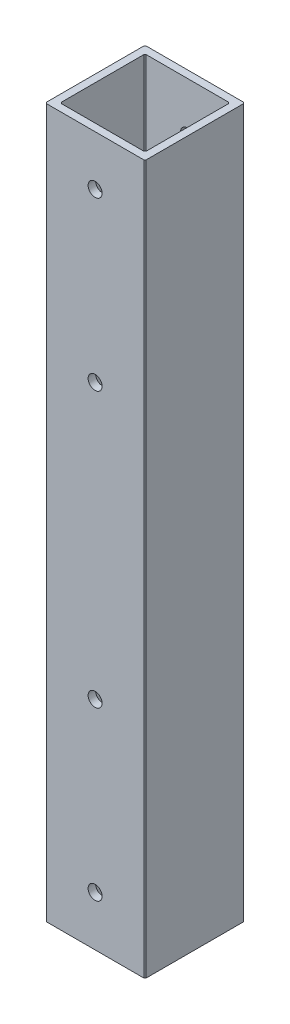
SolidWorks part; units mm, degrees
ref_plane "Front Plane" through (0, 0, 0) normal (0, 0, 1) x (1, 0, 0)
ref_plane "Top Plane" through (0, 0, 0) normal (0, 1, 0) x (1, 0, 0)
ref_plane "Right Plane" through (0, 0, 0) normal (1, 0, 0) x (0, 0, -1)
ref_plane "Plane1" through (170, 0, 0) normal (-1, 0, 0) x (0, -1, 0)
sketch "Sketch1" plane through (170, 0, 0) normal (-1, 0, 0) x (0, -1, 0)
  line L0 (-142, 180) -> (-142, 140)
  line L1 (-142, 140) -> (142, 140)
  line L2 (142, 140) -> (142, 180)
  line L3 (142, 180) -> (-142, 180)
extrude "Boss-Extrude1" add sketch "Sketch1" against normal blind 40
sketch "Sketch2" plane through (0, -142, 0) normal (0, -1, 0) x (1, 0, 0)
  line L0 (207, 143) -> (207, 177)
  line L1 (207, 177) -> (173, 177)
  line L2 (173, 177) -> (173, 143)
  line L3 (173, 143) -> (207, 143)
extrude "Cut-Extrude1" cut sketch "Sketch2" against normal through all
hole_wizard "Ø5.6 (5.6) Diameter Hole1" positions "Sketch4" profile "Sketch3" hole size "Ø5.6" standard "ANSI Metric"
sketch "Sketch4" plane through (0, 0, 140) normal (0, 0, -1) x (-1, 0, 0)
  point P0 (-190, 122)
  point P1 (-190, 55)
  point P2 (-190, -55)
  point P3 (-190, -122)
sketch "Sketch3" plane through (190, 122, 140) normal (1, 0, 0) x (0, 1, 0)
  line L0 (0, 0) -> (0, 3)
  line L1 (0, 3) -> (2.8, 3)
  line L2 (2.8, 3) -> (2.8, 0)
  line L5 (2.8, 0) -> (0, 0)
  line L11 (0, -6.35) -> (0, 107.95) construction
  dimension "Thru Hole Dia." = 5.6
  dimension "Thru Hole Depth" = 3
hole_wizard "Ø5.6 (5.6) Diameter Hole2" positions "Sketch6" profile "Sketch5" hole size "Ø5.6" standard "ANSI Metric"
sketch "Sketch6" plane through (0, 0, 177) normal (0, 0, -1) x (-1, 0, 0)
  point P0 (-190, 122)
  point P1 (-190, 55)
  point P2 (-190, -55)
  point P3 (-190, -122)
sketch "Sketch5" plane through (190, 122, 177) normal (1, 0, 0) x (0, 1, 0)
  line L0 (0, 0) -> (0, 3)
  line L1 (0, 3) -> (2.8, 3)
  line L2 (2.8, 3) -> (2.8, 0)
  line L5 (2.8, 0) -> (0, 0)
  line L11 (0, -6.35) -> (0, 107.95) construction
  dimension "Thru Hole Dia." = 5.6
  dimension "Thru Hole Depth" = 3
chamfer "Chamfer1" distance 0.5 angle 45 8 edges at (210, 0, 140) (170, 0, 140) (170, 0, 180) (173, 0, 177) (210, 0, 180) (207, 0, 143) (207, 0, 177) (173, 0, 143)
